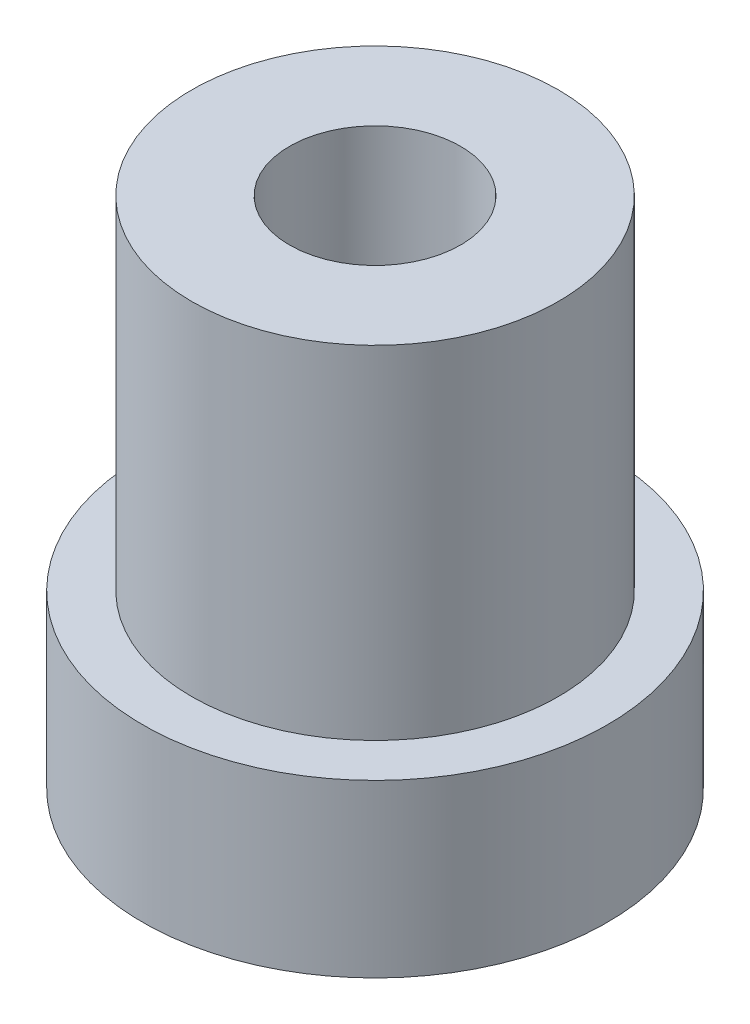
SolidWorks part; units mm, degrees
ref_plane "Front Plane" through (0, 0, 0) normal (0, 0, 1) x (1, 0, 0)
ref_plane "Top Plane" through (0, 0, 0) normal (0, 1, 0) x (1, 0, 0)
ref_plane "Right Plane" through (0, 0, 0) normal (1, 0, 0) x (0, 0, -1)
sketch "Sketch1" plane through (0, 0, 0) normal (0, 1, 0) x (1, 0, 0)
  circle A0 centre (0, 0) radius 3.75
  dimension "D1" = 7.5
extrude "Boss-Extrude1" add sketch "Sketch1" along normal blind 10.5
hole_wizard "Ø3.5 (3.5) Diameter Hole1" positions "Sketch2" profile "Sketch3" hole size "Ø3.5" standard "JIS" end condition through all
sketch "Sketch2" plane through (0, 10.5, 0) normal (0, 1, 0) x (1, 0, 0)
  point P0 (0, 0)
sketch "Sketch3" plane through (0, 10.5, 0) normal (1, 0, 0) x (0, 0, 1)
  line L0 (0, 0) -> (0, 10.5)
  line L1 (0, 10.5) -> (1.75, 10.5)
  line L2 (1.75, 10.5) -> (1.75, 0)
  line L5 (1.75, 0) -> (0, 0)
  line L11 (0, -6.35) -> (0, 107.95) construction
  dimension "Thru Hole Dia." = 3.5
  dimension "Thru Hole Depth" = 10.5
sketch "Sketch4" plane through (0, 0, 0) normal (0, -1, 0) x (1, 0, 0)
  circle A0 centre (0, 0) radius 4.75
  dimension "D1" = 9.5
extrude "Boss-Extrude2" add sketch "Sketch4" against normal blind 3.5
